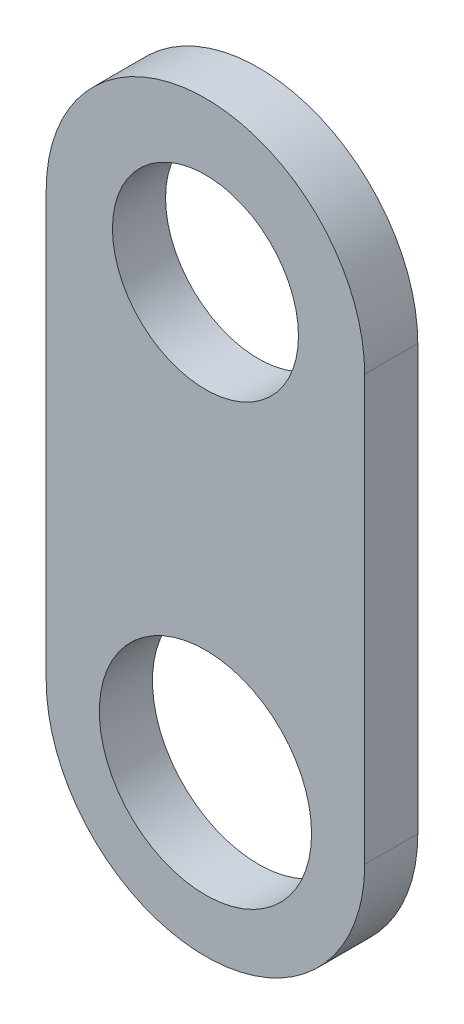
SolidWorks part; units mm, degrees
material "6061-T6 (SS)"
ref_plane "Front Plane" through (0, 0, 0) normal (0, 0, 1) x (1, 0, 0)
ref_plane "Top Plane" through (0, 0, 0) normal (0, 1, 0) x (1, 0, 0)
ref_plane "Right Plane" through (0, 0, 0) normal (1, 0, 0) x (0, 0, -1)
sketch "Sketch2" plane through (0, 0, 0) normal (0, 0, 1) x (1, 0, 0)
  line L0 (0, 0) -> (0, 50.8) construction
  line L1 (-19.05, 0) -> (-19.05, 50.8)
  line L2 (19.05, 0) -> (19.05, 50.8)
  arc A0 (-19.05, 0) -> (19.05, 0) centre (0, 0) ccw
  arc A1 (19.05, 50.8) -> (-19.05, 50.8) centre (0, 50.8) ccw
  circle A2 centre (0, 50.8) radius 11.1252
  circle A3 centre (0, 0) radius 12.6937
  point P3 (0, 25.4)
  dimension "D3" = 22.2504
  dimension "D4" = 25.3873
  dimension "D1" = 38.1
  dimension "D2" = 50.8
extrude "Boss-Extrude1" add sketch "Sketch2" along normal mid plane 6.35
equation "\"Link Width\"= 1.5in"
equation "\"Hole Spacing\"= 2in"
equation "\"Link Thickness\"= 0.25in"
equation "\"Bracket Bar Diameter\"= \"Bar Diameter\""
equation "\"Second Shaft Diameter\"= 1in"
equation "\"D1@Sketch2\"=\"Link Width\""
equation "\"D2@Sketch2\"=\"Hole Spacing\""
equation "\"D1@Boss-Extrude1\"=\"Link Thickness\""
equation "\"D3@Sketch2\" = \"Bracket Hole Diameter\""
equation "\"D4@Sketch2\" = \"Shaft Hole Diameter\""
equation "\"Bar Diameter\" = \"Minimum Bar Diameter\"+\"Diameter Allowance\""
equation "\"Bracket Hole Diameter\"= \"Bracket Bar Diameter\" + 0.001in"
equation "\"Shaft Hole Diameter\"= \"Second Shaft Diameter\" - 0.0005in"
